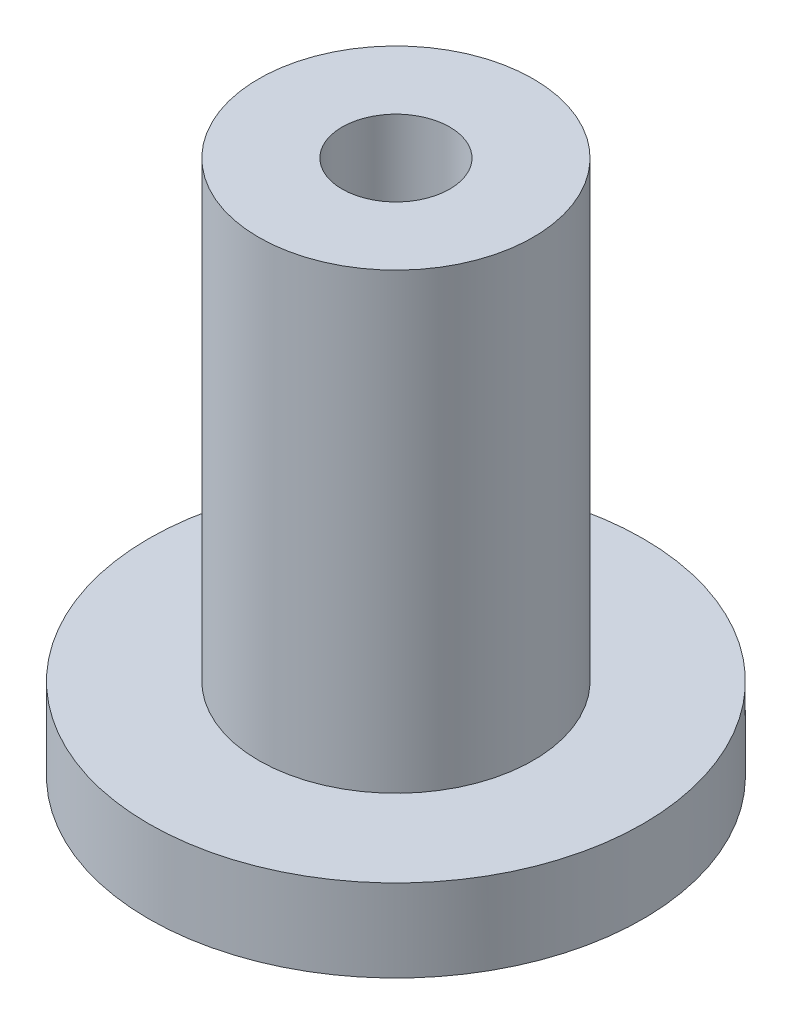
SolidWorks part; units mm, degrees
ref_plane "Front Plane" through (0, 0, 0) normal (0, 0, 1) x (1, 0, 0)
ref_plane "Top Plane" through (0, 0, 0) normal (0, 1, 0) x (1, 0, 0)
ref_plane "Right Plane" through (0, 0, 0) normal (1, 0, 0) x (0, 0, -1)
sketch "Sketch1" plane through (0, 0, 0) normal (0, 1, 0) x (1, 0, 0)
  circle A0 centre (0, 0) radius 3.1115
  circle A1 centre (0, 0) radius 7.9375
  dimension "D1" = 15.875
  dimension "D2" = 6.223
extrude "Boss-Extrude1" add sketch "Sketch1" along normal blind 26.1937
sketch "Sketch2" plane through (0, 0, 0) normal (0, -1, 0) x (1, 0, 0)
  circle A2 centre (0, 0) radius 14.2875
  circle A3 centre (0, 0) radius 14.2875
  dimension "D1" = 6.35
extrude "Boss-Extrude2" add sketch "Sketch2" along normal blind 6.35
chamfer "Chamfer1" distance 1.5875 angle 70 1 edges at (0, -6.35, -14.2875)
sketch "Sketch3" plane through (0, -6.35, 0) normal (0, -1, 0) x (1, 0, 0)
  circle A0 centre (0, 0) radius 4.6736
  dimension "D1" = 9.3472
extrude "Cut-Extrude1" cut sketch "Sketch3" against normal blind 6.477
sketch "Sketch4" [suppressed] plane through (0, 26.1937, 0) normal (0, 1, 0) x (1, 0, 0)
  circle A0 centre (0, 0) radius 7.9375 construction
  circle A1 centre (0, 0) radius 7.9375
extrude "Cut-Extrude2" [suppressed] cut sketch "Sketch4" against normal blind 26.5906
sketch "Sketch5" [suppressed] plane through (0, -6.35, 0) normal (0, -1, 0) x (1, 0, 0)
  line L1 (6.3058, 0) -> (3.1529, 5.461)
  line L2 (3.1529, 5.461) -> (-3.1529, 5.461)
  line L3 (-3.1529, 5.461) -> (-6.3058, 0)
  line L4 (-6.3058, 0) -> (-3.1529, -5.461)
  line L5 (-3.1529, -5.461) -> (3.1529, -5.461)
  line L6 (3.1529, -5.461) -> (6.3058, 0)
  circle A0 centre (0, 0) radius 5.461 construction
  dimension "D1" = 10.922
extrude "Cut-Extrude4" [suppressed] cut sketch "Sketch5" against normal blind 3.175
sketch "Sketch7" [suppressed] plane through (0, -0.3969, 0) normal (0, 1, 0) x (1, 0, 0)
  circle A0 centre (0, 0) radius 3.175
  dimension "D1" = 6.35
extrude "Cut-Extrude5" [suppressed] cut sketch "Sketch7" against normal blind 3.175
